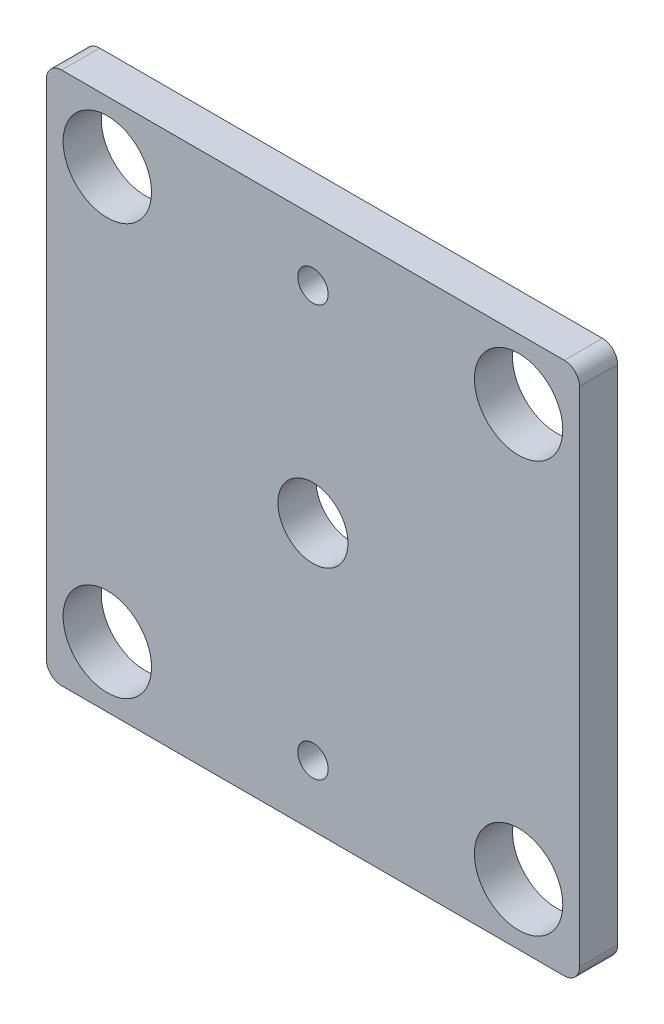
SolidWorks part; units mm, degrees
ref_plane "Front" through (0, 0, 0) normal (0, 0, 1) x (1, 0, 0)
ref_plane "Top" through (0, 0, 0) normal (0, 1, 0) x (1, 0, 0)
ref_plane "Right" through (0, 0, 0) normal (1, 0, 0) x (0, 0, -1)
sketch "Sketch1" plane through (0, 0, 0) normal (0, 0, 1) x (1, 0, 0)
  line L1 (35, -35) -> (-35, -35)
  line L2 (35, -35) -> (35, 35)
  line L3 (35, 35) -> (-35, 35)
  line L4 (-35, -35) -> (-35, 35)
  line L5 (35, -35) -> (-35, 35) construction
  line L6 (35, 35) -> (-35, -35) construction
  circle A0 centre (-27, 27) radius 5.8
  circle A1 centre (27, 27) radius 5.8
  circle A2 centre (27, -27) radius 5.8
  circle A3 centre (-27, -27) radius 5.8
  circle A4 centre (0, 0) radius 4.6
  circle A5 centre (0, 27) radius 2
  circle A6 centre (0, -27) radius 2
  point P0 (0, 0)
  dimension "D3" = 11.6
  dimension "D4" = 11.6
  dimension "D5" = 11.6
  dimension "D6" = 11.6
  dimension "D8" = 9.2
  dimension "D9" = 4
  dimension "D1" = 70
  dimension "D2" = 70
  dimension "D7" = 8
extrude "Boss-Extrude1" add sketch "Sketch1" along normal blind 5
fillet "Fillet1" radius 2 3 edges at (35, -35, 2.5) (35, 35, 2.5) (-35, 35, 2.5)
fillet "Fillet2" radius 2 1 edges at (-35, -35, 2.5)
